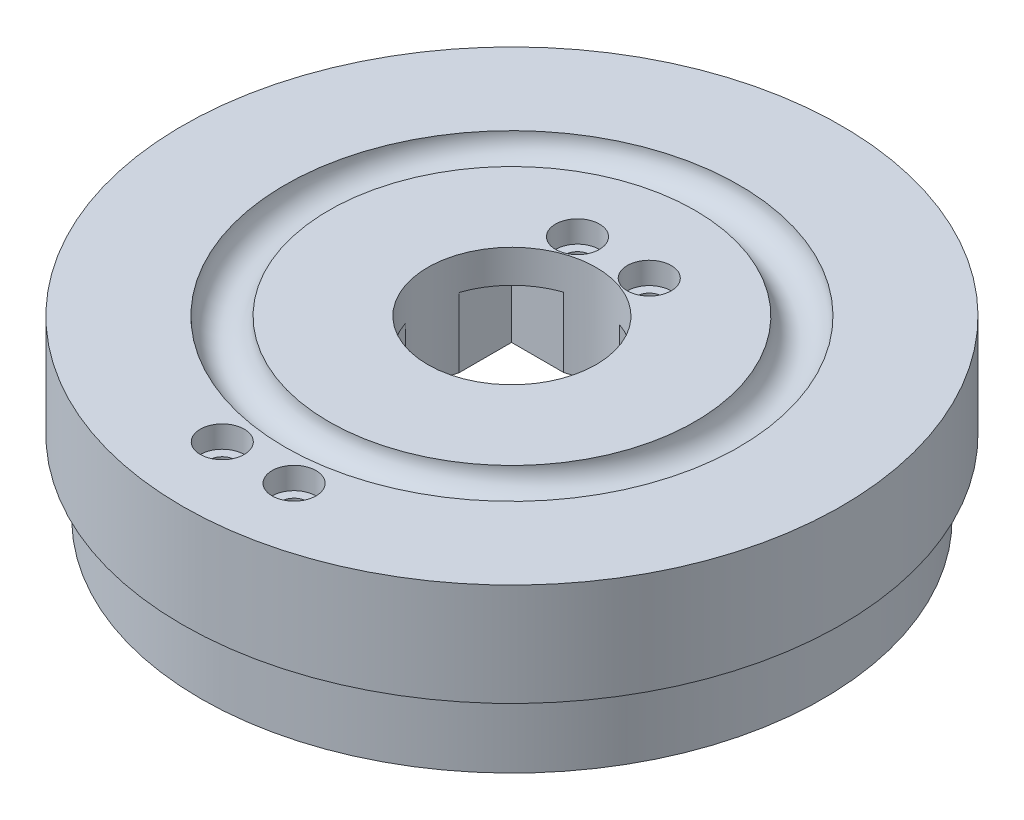
SolidWorks part; units mm, degrees
ref_plane "Front Plane" through (0, 0, 0) normal (0, 0, 1) x (1, 0, 0)
ref_plane "Top Plane" through (0, 0, 0) normal (0, 1, 0) x (1, 0, 0)
ref_plane "Right Plane" through (0, 0, 0) normal (1, 0, 0) x (0, 0, -1)
sketch "Sketch1" plane through (0, 0, 0) normal (0, 1, 0) x (1, 0, 0)
  circle A0 centre (0, 0) radius 45
  circle A1 centre (0, 0) radius 11.5
  dimension "D1" = 90
  dimension "D2" = 23
extrude "Boss-Extrude1" add sketch "Sketch1" along normal blind 14
sketch "Sketch3" plane through (0, 0, 0) normal (0, 0, 1) x (1, 0, 0)
  line L0 (45, 14) -> (-45, 14) construction
  circle A0 centre (-28, 14) radius 3
  dimension "D2" = 6
  dimension "D1" = 28
ref_axis "Axis1" through (0, 14, 0) along (0, -1, 0)
revolve "Cut-Revolve1" cut sketch "Sketch3" angle 360 about axis through (0, 14, 0) along (0, -1, 0)
sketch "Sketch6" plane through (0, 14, 0) normal (0, 1, 0) x (1, 0, 0)
  circle A0 centre (-4.9, -34.65) radius 3
  circle A1 centre (4.9, -34.65) radius 3
  circle A2 centre (-4.9, 13.85) radius 3
  circle A3 centre (4.9, 13.85) radius 3
  dimension "D1" = 6
  dimension "D2" = 6
  dimension "D3" = 6
  dimension "D4" = 6
extrude "Cut-Extrude3" cut sketch "Sketch6" against normal blind 3
sketch "Sketch7" plane through (0, 0, 0) normal (0, -1, 0) x (1, 0, 0)
  circle A0 centre (4.9, 34.65) radius 1.75
  circle A1 centre (-4.9, 34.65) radius 1.75
  circle A2 centre (4.9, -13.85) radius 1.75
  circle A3 centre (-4.9, -13.85) radius 1.75
  dimension "D1" = 3.5
  dimension "D2" = 3.5
  dimension "D3" = 3.5
  dimension "D4" = 3.5
extrude "Cut-Extrude4" cut sketch "Sketch7" against normal blind 13
sketch "Sketch8" plane through (0, 0, 0) normal (0, -1, 0) x (1, 0, 0)
  line L0 (4.9, 34.65) -> (4.9, -13.85) construction
  line L1 (-10.9, -10.85) -> (10.9, -10.85)
  line L2 (-10.9, -10.85) -> (-10.9, 31.65)
  line L3 (-10.9, 31.65) -> (10.9, 31.65)
  line L4 (10.9, -10.85) -> (10.9, 31.65)
  line L5 (-4.9, 34.65) -> (-4.9, -33.8264) construction
  dimension "D1" = 6
  dimension "D2" = 6
  dimension "D3" = 3
  dimension "D4" = 3
extrude "Cut-Extrude7" cut sketch "Sketch8" against normal blind 9.5
sketch "Sketch9" plane through (0, 0, 0) normal (0, -1, 0) x (1, 0, 0)
  circle A0 centre (0, 0) radius 45
  circle A1 centre (0, 0) radius 42.5
  circle A2 centre (0, 0) radius 40.5
  dimension "D1" = 2.5
  dimension "D2" = 2
  dimension "D3" = 90
extrude "Boss-Extrude2" add sketch "Sketch9" along normal blind 10 contours A1 A2
